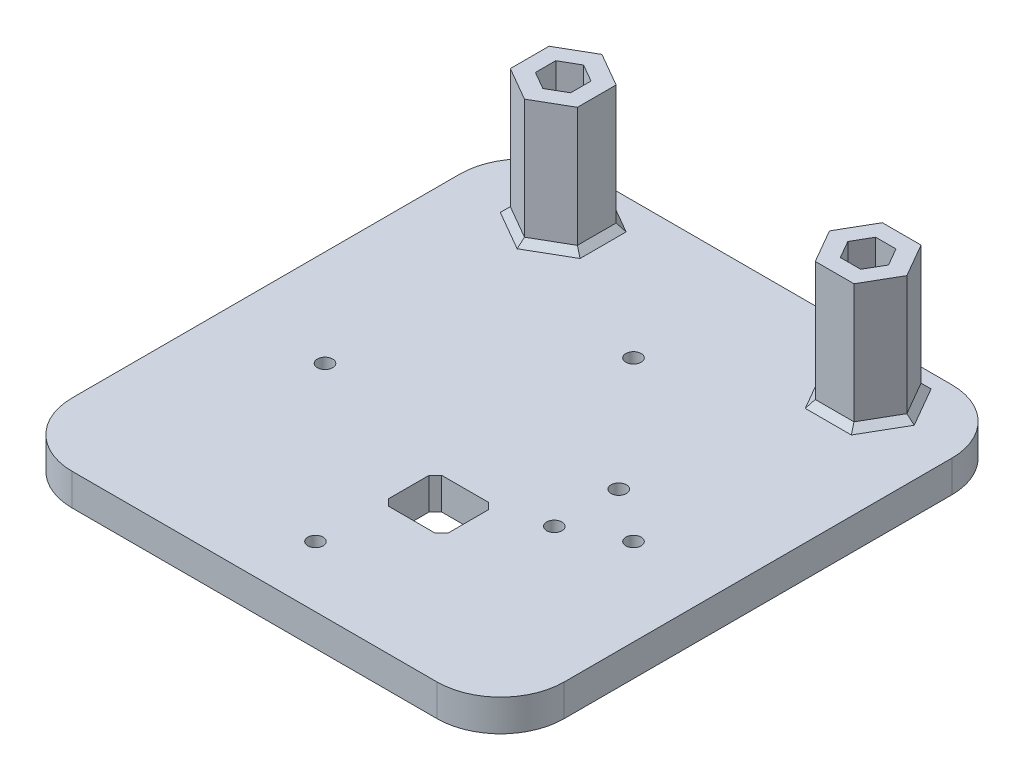
SolidWorks part; units mm, degrees
material "Custom Plastic"
ref_plane "Front Plane" through (0, 0, 0) normal (0, 0, 1) x (1, 0, 0)
ref_plane "Top Plane" through (0, 0, 0) normal (0, 1, 0) x (1, 0, 0)
ref_plane "Right Plane" through (0, 0, 0) normal (1, 0, 0) x (0, 0, -1)
sketch "Sketch1" plane through (0, 0, 0) normal (0, 1, 0) x (1, 0, 0)
  line L0 (0, 40.4682) -> (0, -40.4682)
  line L1 (-38.6775, -40.4682) -> (38.6775, -40.4682)
  line L2 (-38.6775, -40.4682) -> (-38.6775, 40.4682)
  line L3 (-38.6775, 40.4682) -> (38.6775, 40.4682)
  line L4 (38.6775, -40.4682) -> (38.6775, 40.4682)
  line L5 (-38.6775, -40.4682) -> (38.6775, 40.4682) construction
  line L6 (-38.6775, 40.4682) -> (38.6775, -40.4682) construction
  line L8 (-21.2287, 33.6513) -> (-24, 35.2513)
  line L9 (-24, 35.2513) -> (-26.7713, 33.6513)
  line L10 (-26.7713, 33.6513) -> (-26.7713, 30.4513)
  line L11 (-26.7713, 30.4513) -> (-24, 28.8513)
  line L12 (-24, 28.8513) -> (-21.2287, 30.4513)
  line L13 (-21.2287, 30.4513) -> (-21.2287, 33.6513)
  line L14 (27.2, 31.9941) -> (25.6, 34.7654)
  line L15 (25.6, 34.7654) -> (22.4, 34.7654)
  line L16 (22.4, 34.7654) -> (20.8, 31.9941)
  line L17 (20.8, 31.9941) -> (22.4, 29.2228)
  line L18 (22.4, 29.2228) -> (25.6, 29.2228)
  line L19 (25.6, 29.2228) -> (27.2, 31.9941)
  circle A0 centre (-24, 32.0513) radius 2.7713 construction
  circle A1 centre (24, 31.9941) radius 2.7713 construction
  point P0 (0, 0)
  dimension "D1" = 3.2
  dimension "D2" = 24
  dimension "D3" = 3.2
  dimension "D4" = 24
extrude "Boss-Extrude1" add sketch "Sketch1" along normal blind 5 contours L1 L4 L3 L0 L19 L18 L17 L16 L15 L14 | L3 L2 L1 L0 L13 L12 L11 L10 L9 L8
fillet "Fillet1" radius 10 4 edges at (-38.6775, 2.5, -40.4682) (-38.6775, 2.5, 40.4682) (38.6775, 2.5, -40.4682) (38.6775, 2.5, 40.4682)
sketch "Sketch2" plane through (0, 0, 0) normal (0, -1, 0) x (-1, 0, 0)
  point P0 (-25, -5.8984)
  point P2 (0, -30.8984)
  point P4 (23.5, -5.8984)
  point P6 (0, 19.1016)
  dimension "D1" = 48.5
  dimension "D2" = 50
  dimension "D3" = 25
  dimension "D4" = 25
sketch "Sketch6" plane through (0, 0, 0) normal (0, -1, 0) x (1, 0, 0)
  circle A0 centre (0, 5.8197) radius 3.2
  dimension "D1" = 6.4
extrude "Cut-Extrude1" [suppressed] cut sketch "Sketch6" against normal up to surface (5 mm away)
sketch "Sketch7" plane through (0, 5, 0) normal (0, 1, 0) x (1, 0, 0)
  line L12 (-18.7287, 35.0947) -> (-24, 38.1381)
  line L13 (-18.7287, 29.0079) -> (-18.7287, 35.0947)
  line L14 (-24, 25.9645) -> (-18.7287, 29.0079)
  line L15 (-29.2713, 29.0079) -> (-24, 25.9645)
  line L16 (-29.2713, 35.0947) -> (-29.2713, 29.0079)
  line L17 (-24, 38.1381) -> (-29.2713, 35.0947)
  line L18 (-18.7287, 35.0947) -> (-24, 38.1381)
  line L19 (-18.7287, 29.0079) -> (-18.7287, 35.0947)
  line L20 (-24, 25.9645) -> (-18.7287, 29.0079)
  line L21 (-29.2713, 29.0079) -> (-24, 25.9645)
  line L22 (-29.2713, 35.0947) -> (-29.2713, 29.0079)
  line L23 (-24, 38.1381) -> (-29.2713, 35.0947)
  line L30 (27.0434, 37.2654) -> (20.9566, 37.2654)
  line L31 (20.9566, 37.2654) -> (17.9132, 31.9941)
  line L32 (17.9132, 31.9941) -> (20.9566, 26.7228)
  line L33 (27.0434, 26.7228) -> (30.0868, 31.9941)
  line L34 (20.9566, 26.7228) -> (27.0434, 26.7228)
  line L35 (30.0868, 31.9941) -> (27.0434, 37.2654)
  line L36 (27.0434, 37.2654) -> (20.9566, 37.2654)
  line L37 (20.9566, 37.2654) -> (17.9132, 31.9941)
  line L38 (17.9132, 31.9941) -> (20.9566, 26.7228)
  line L39 (27.0434, 26.7228) -> (30.0868, 31.9941)
  line L40 (20.9566, 26.7228) -> (27.0434, 26.7228)
  line L41 (30.0868, 31.9941) -> (27.0434, 37.2654)
  line L48 (-21.2287, 33.6513) -> (-24, 35.2513) construction
  line L49 (-24, 35.2513) -> (-26.7713, 33.6513) construction
  line L50 (-26.7713, 33.6513) -> (-26.7713, 30.4513) construction
  line L51 (-26.7713, 30.4513) -> (-24, 28.8513) construction
  line L52 (-24, 28.8513) -> (-21.2287, 30.4513) construction
  line L53 (-21.2287, 30.4513) -> (-21.2287, 33.6513) construction
  line L54 (-21.2287, 30.4513) -> (-21.2287, 33.6513)
  line L55 (-24, 28.8513) -> (-21.2287, 30.4513)
  line L56 (-26.7713, 30.4513) -> (-24, 28.8513)
  line L57 (-26.7713, 33.6513) -> (-26.7713, 30.4513)
  line L58 (-24, 35.2513) -> (-26.7713, 33.6513)
  line L59 (-21.2287, 33.6513) -> (-24, 35.2513)
  line L60 (22.4, 34.7654) -> (20.8, 31.9941) construction
  line L61 (25.6, 34.7654) -> (22.4, 34.7654) construction
  line L62 (27.2, 31.9941) -> (25.6, 34.7654) construction
  line L63 (25.6, 29.2228) -> (27.2, 31.9941) construction
  line L64 (22.4, 29.2228) -> (25.6, 29.2228) construction
  line L65 (20.8, 31.9941) -> (22.4, 29.2228) construction
  line L66 (25.6, 34.7654) -> (22.4, 34.7654)
  line L67 (22.4, 34.7654) -> (20.8, 31.9941)
  line L68 (20.8, 31.9941) -> (22.4, 29.2228)
  line L69 (22.4, 29.2228) -> (25.6, 29.2228)
  line L70 (25.6, 29.2228) -> (27.2, 31.9941)
  line L71 (27.2, 31.9941) -> (25.6, 34.7654)
  dimension "D1" = 2.5
  dimension "D2" = 2.5
extrude "Boss-Extrude2" add sketch "Sketch7" along normal blind 19.8
chamfer "Chamfer1" distance 1 angle 45 12 edges at (-26.6356, 5, -36.6164) (-29.2713, 5, -32.0513) (-26.6356, 5, -27.4862) (-21.3644, 5, -27.4862) (-18.7287, 5, -32.0513) (-21.3644, 5, -36.6164) (19.4349, 5, -34.6297) (19.4349, 5, -29.3584) (24, 5, -26.7228) (28.5651, 5, -29.3584) (28.5651, 5, -34.6297) (24, 5, -37.2654)
sketch "Sketch9" [suppressed] plane through (0, 5, 0) normal (0, 1, 0) x (1, 0, 0)
  line L1 (-13.4446, -12.3197) -> (-8.4446, -12.3197)
  line L2 (-13.4446, -12.3197) -> (-13.4446, 0.6803)
  line L3 (-13.4446, 0.6803) -> (-8.4446, 0.6803)
  line L4 (-8.4446, -12.3197) -> (-8.4446, 0.6803)
  line L6 (-8.4446, -3.9924) -> (-8.4446, -7.6924) construction
  line L7 (-8.4446, 0.6576) -> (-8.4446, -12.3424) construction
  circle A0 centre (0, -5.8197) radius 3.2 construction
  circle A1 centre (0, -5.8197) radius 3.2
  point P8 (-8.4446, -5.8197)
  point P15 (-13.4446, -5.8197)
  dimension "D1" = 5
  dimension "D2" = 13
extrude "Boss-Extrude3" [suppressed] add sketch "Sketch9" along normal blind 20 contours L1 L4 L3 L2
sketch "Sketch11" [suppressed] plane through (-8.4446, 0, 0) normal (1, 0, 0) x (0, 0, -1)
  line L0 (0.6576, 5) -> (-12.3424, 5) construction
  line L3 (0.6803, 25) -> (0.6803, 5) construction
  circle A0 centre (-2.3197, 9) radius 1.45
  circle A3 centre (-9.3197, 19) radius 1.45
  dimension "D1" = 2.9
  dimension "D2" = 2.9
  dimension "D3" = 4
  dimension "D4" = 10
  dimension "D5" = 7
  dimension "D6" = 3
extrude "Cut-Extrude2" [suppressed] cut sketch "Sketch11" against normal up to next
chamfer "Chamfer2" [suppressed] distance 2 angle 45
hole_wizard "CSK for M2 Flat Head Machine Screw1" positions "Sketch2" profile "Sketch3" countersink size "M2" standard "ANSI Metric" end condition up to next
sketch "Sketch3" plane through (25, 0, 5.8984) normal (1, 0, 0) x (0, 0, -1)
  line L0 (0, 0) -> (0, 5)
  line L1 (0, 5) -> (1.2, 5)
  line L2 (1.2, 5) -> (1.2, 1)
  line L3 (1.2, 1) -> (2.2, 0)
  line L5 (2.2, 0) -> (0, 0)
  line L6 (-1.2, 1) -> (-2.2, 0) construction
  line L11 (0, -6.35) -> (0, 107.95) construction
  dimension "Thru Hole Dia." = 2.4
  dimension "Thru Hole Depth" = 5
  dimension "Near C'Sink Dia." = 4.4
  dimension "Near C'Sink Angle" = 90
sketch "Sketch12" plane through (0, 0, 0) normal (0, -1, 0) x (1, 0, 0)
  line L1 (9.2758, 20.3535) -> (-0.0784, 20.3535)
  line L2 (9.2758, 20.3535) -> (9.2758, 11.9661)
  line L3 (9.2758, 11.9661) -> (-0.0784, 11.9661)
  line L4 (-0.0784, 20.3535) -> (-0.0784, 11.9661)
extrude "Cut-Extrude3" cut sketch "Sketch12" against normal up to next
chamfer "Chamfer3" distance 1 angle 45 4 edges at (9.2758, 2.5, 11.9661) (-0.0784, 2.5, 11.9661) (-0.0784, 2.5, 20.3535) (9.2758, 2.5, 20.3535)
sketch "Sketch15" plane through (0, 5, 0) normal (0, 1, 0) x (1, 0, 0)
  circle A0 centre (16.714, -10.0602) radius 1.2
  circle A1 centre (16.714, 0.0685) radius 1.2
extrude "Cut-Extrude4" cut sketch "Sketch15" against normal blind 10
